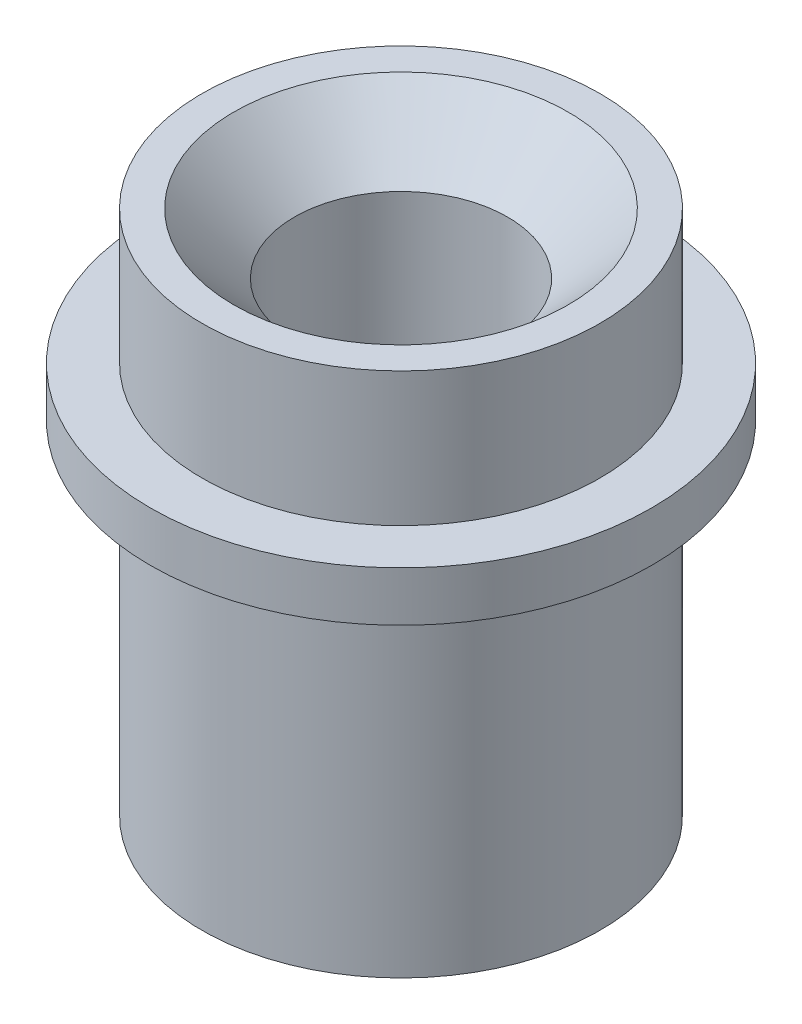
SolidWorks part; units mm, degrees
material "黄铜"
ref_plane "前视基准面" through (0, 0, 0) normal (0, 0, 1) x (1, 0, 0)
ref_plane "上视基准面" through (0, 0, 0) normal (0, 1, 0) x (1, 0, 0)
ref_plane "右视基准面" through (0, 0, 0) normal (1, 0, 0) x (0, 0, -1)
sketch "草图1" plane through (0, 0, 0) normal (0, 0, 1) x (1, 0, 0)
  line L0 (0, 0) -> (0, 19.2962) construction
  line L1 (0, 0) -> (3.12, 0)
  line L2 (3.12, 0) -> (3.12, 5.36)
  line L3 (3.12, 5.36) -> (3.93, 5.36)
  line L4 (3.93, 5.36) -> (3.93, 6.14)
  line L5 (3.93, 6.14) -> (3.12, 6.14)
  line L6 (3.12, 6.14) -> (3.12, 8.24)
  line L7 (3.12, 8.24) -> (0, 8.24)
  line L10 (0, 8.24) -> (0, 0)
  dimension "D3" = 8.24
  dimension "D4" = 6.14
  dimension "D5" = 0.78
  dimension "D6" = 3.12
  dimension "D7" = 3.93
revolve "旋转1" add sketch "草图1" angle 360 about L0
sketch "草图2" plane through (0, 0, 0) normal (0, -1, 0) x (1, 0, 0)
  circle A0 centre (0, 0) radius 1.67
  dimension "D1" = 3.34
extrude "切除-拉伸1" cut sketch "草图2" against normal through all
cosmetic thread "装饰螺纹线1" parameters "D2"=5
sketch "草图4" plane through (0, 0, 0) normal (0, 0, 1) x (1, 0, 0)
  line L0 (2.62, 0) -> (1.67, 0.95)
  line L1 (-3.12, 0) -> (3.12, 0) construction
  line L2 (1.67, 0.95) -> (0, 0.95)
  line L3 (0, 0.95) -> (0, 0)
  line L4 (0, 0) -> (2.62, 0)
  line L5 (2.62, 8.24) -> (1.67, 7.29)
  line L6 (3.12, 8.24) -> (-3.12, 8.24) construction
  line L7 (1.67, 7.29) -> (0, 7.29)
  line L8 (0, 8.24) -> (0, 6.14) construction
  line L9 (0, 7.29) -> (0, 8.24)
  line L10 (0, 8.24) -> (2.62, 8.24)
  dimension "D1" = 45
  dimension "D2" = 2.62
  dimension "D3" = 1.67
  dimension "D4" = 1.67
  dimension "D5" = 2.62
  dimension "D6" = 45
revolve "切除-旋转1" cut sketch "草图4" angle 360 about axis through (0, 0, 0) along (0, -1, 0)
